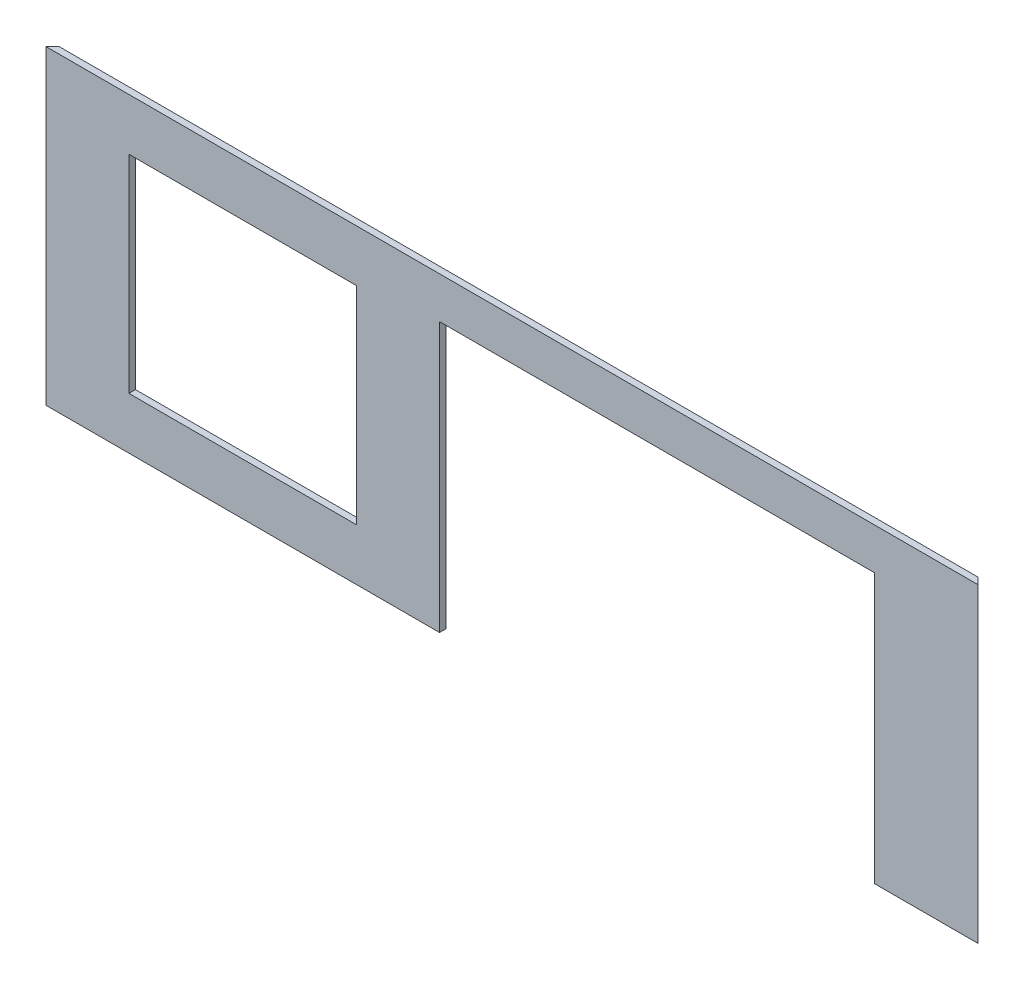
SolidWorks part; units mm, degrees
ref_plane "Front Plane" through (0, 0, 0) normal (0, 0, 1) x (1, 0, 0)
ref_plane "Top Plane" through (0, 0, 0) normal (0, 1, 0) x (1, 0, 0)
ref_plane "Right Plane" through (0, 0, 0) normal (1, 0, 0) x (0, 0, -1)
sketch "Sketch1" plane through (0, 0, 0) normal (0, 0, 1) x (1, 0, 0)
  line L1 (0, 0) -> (450, 0)
  line L2 (0, 0) -> (0, 150)
  line L3 (0, 150) -> (450, 150)
  line L4 (450, 0) -> (450, 150)
  dimension "D1" = 450
  dimension "D2" = 150
extrude "Boss-Extrude1" add sketch "Sketch1" along normal blind 3.175
sketch "Sketch2" plane through (0, 150, 0) normal (0, 1, 0) x (1, 0, 0)
  line L0 (0, -3.175) -> (3.175, 0)
  line L1 (450, 0) -> (0, 0) construction
  line L2 (3.175, 0) -> (0, 0)
  line L3 (0, 0) -> (0, -3.175)
  line L4 (450, -3.175) -> (446.825, 0)
  line L5 (446.825, 0) -> (450, 0)
  line L6 (450, 0) -> (450, -3.175)
extrude "Cut-Extrude1" cut sketch "Sketch2" against normal through all
sketch "Sketch3" plane through (0, 0, 3.175) normal (0, 0, 1) x (1, 0, 0)
  line L0 (0, 0) -> (450, 0) construction
  line L1 (400, 0) -> (190, 0)
  line L2 (400, 0) -> (400, 130)
  line L3 (400, 130) -> (190, 130)
  line L4 (190, 0) -> (190, 130)
  line L5 (450, 150) -> (0, 150) construction
  line L6 (450, 0) -> (450, 150) construction
  line L7 (0, 150) -> (0, 0) construction
  line L8 (40, 25) -> (150, 25)
  line L9 (40, 25) -> (40, 125)
  line L10 (40, 125) -> (150, 125)
  line L11 (150, 25) -> (150, 125)
  line L12 (95, 125) -> (95, 150) construction
  line L13 (95, 25) -> (95, 0) construction
  dimension "D1" = 20
  dimension "D2" = 50
  dimension "D3" = 110
  dimension "D4" = 40
  dimension "D5" = 210
  dimension "D6" = 100
extrude "Cut-Extrude2" cut sketch "Sketch3" against normal through all
